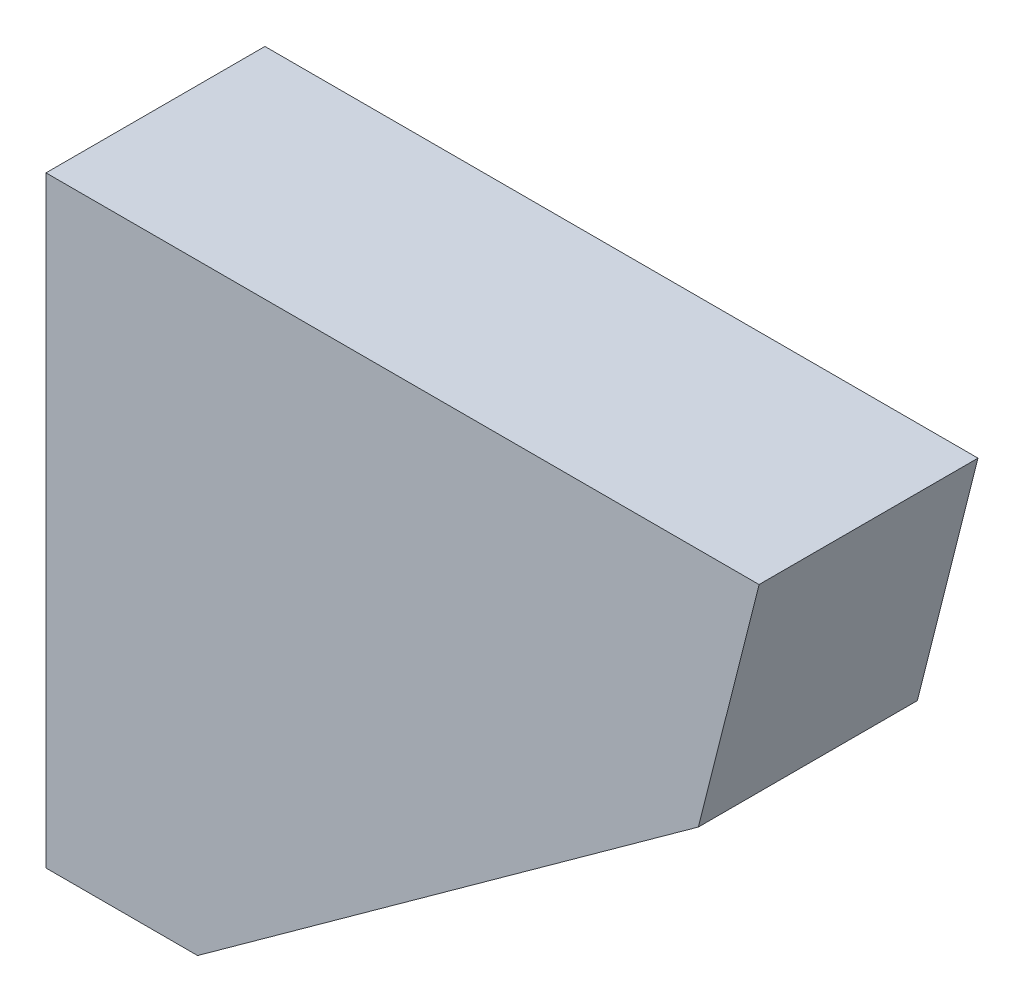
SolidWorks part; units mm, degrees
ref_plane "Спереди" through (0, 0, 0) normal (0, 0, 1) x (1, 0, 0)
ref_plane "Сверху" through (0, 0, 0) normal (0, 1, 0) x (1, 0, 0)
ref_plane "Справа" through (0, 0, 0) normal (1, 0, 0) x (0, 0, -1)
sketch "Эскиз1" plane through (0, 0, 0) normal (0, 0, 1) x (1, 0, 0)
  line L0 (0, 0) -> (0, -26)
  line L1 (0, 0) -> (36, 0)
  line L2 (36, 0) -> (0, -26)
extrude "Вытянуть1" add sketch "Эскиз1" along normal blind 8
chamfer "Фаска1" distance 4 angle 90 1 edges at (0, -26, 4)
chamfer "Фаска2" distance 15 angle 40 1 edges at (36, 0, 4)
